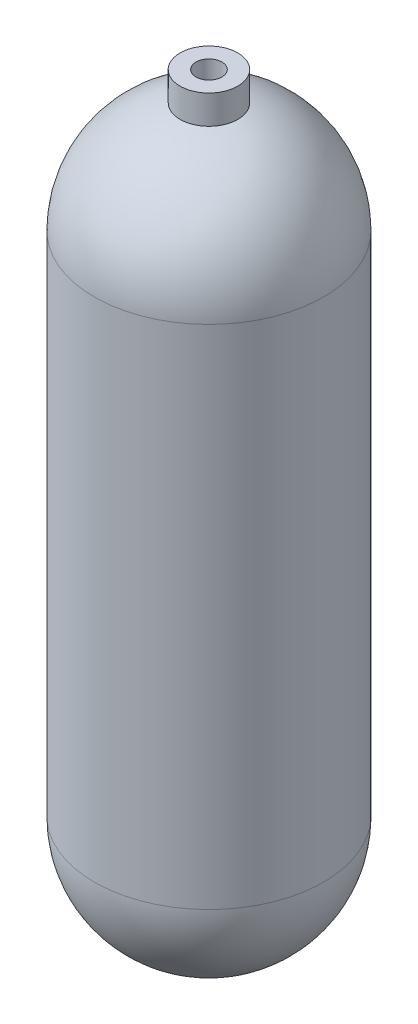
SolidWorks part; units mm, degrees
ref_plane "Front Plane" through (0, 0, 0) normal (0, 0, 1) x (1, 0, 0)
ref_plane "Top Plane" through (0, 0, 0) normal (0, 1, 0) x (1, 0, 0)
ref_plane "Right Plane" through (0, 0, 0) normal (1, 0, 0) x (0, 0, -1)
sketch "Sketch1" plane through (0, 0, 0) normal (0, 0, 1) x (1, 0, 0)
  line L0 (0, 0) -> (0, -22.4446) construction
  line L1 (-9, 0) -> (-9, -20)
  line L2 (-20, 0) -> (-20, -20)
  line L3 (-79.5057, -448.5) -> (-79.5057, -96.9446)
  line L4 (-20, 0) -> (-9, 0)
  line L5 (-9, -20) -> (0, -20)
  line L6 (0, -20) -> (0, -528)
  arc A1 (-20, -20) -> (-79.5057, -96.9446) centre (-0.0057, -96.9446) ccw
  arc A3 (-79.5057, -448.5) -> (0, -528) centre (-0.0057, -448.5) ccw
  dimension "D5" = 528
  dimension "D1" = 0
  dimension "D2" = 9
  dimension "D4" = 20
  dimension "D3" = 11
revolve "Revolve1" add sketch "Sketch1" angle 360 about L0
